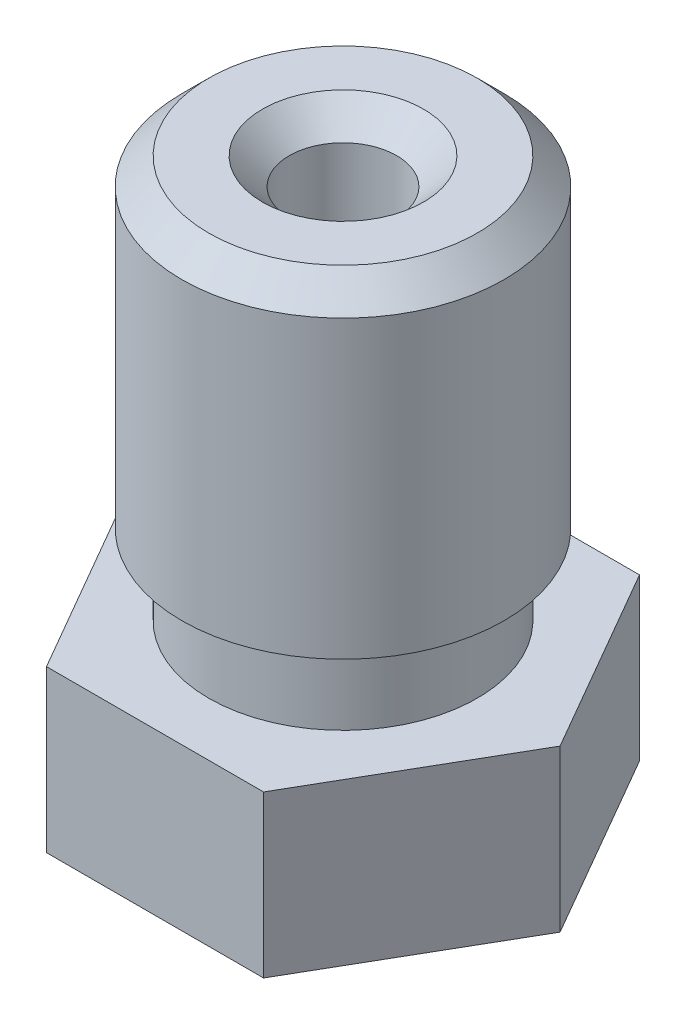
SolidWorks part; units mm, degrees
ref_plane "Спереди" through (0, 0, 0) normal (0, 0, 1) x (1, 0, 0)
ref_plane "Сверху" through (0, 0, 0) normal (0, 1, 0) x (1, 0, 0)
ref_plane "Справа" through (0, 0, 0) normal (1, 0, 0) x (0, 0, -1)
ref_plane "Плоскость1" through (0, 0, 0) normal (0, 0, -1) x (-1, 0, 0)
sketch "Эскиз1" plane through (0, 0, 0) normal (0, 0, -1) x (-1, 0, 0)
  line L0 (-3, 4.5) -> (0, 4.5)
  line L1 (0, 4.5) -> (0, 10.5)
  line L2 (0, 10.5) -> (-3, 10.5)
  line L3 (-3, 10.5) -> (-3, 4.5)
  line L4 (0, 4.5) -> (0, 10.5) construction
revolve "Повернуть1" add sketch "Эскиз1" angle 360 about L4
sketch "Эскиз2" plane through (0, 4.5, 0) normal (0, -1, 0) x (1, 0, 0)
  circle A0 centre (0, 0) radius 2.5
extrude "Бобышка-Вытянуть1" add sketch "Эскиз2" along normal blind 1.5
ref_plane "Плоскость2" through (0, 3, 0) normal (0, 1, 0) x (1, 0, 0)
sketch "Эскиз3" plane through (0, 3, 0) normal (0, 1, 0) x (1, 0, 0)
  line L0 (-2.0207, -3.5) -> (2.0207, -3.5)
  line L1 (2.0207, -3.5) -> (4.0415, 0)
  line L2 (4.0415, 0) -> (2.0207, 3.5)
  line L3 (2.0207, 3.5) -> (-2.0207, 3.5)
  line L4 (-2.0207, 3.5) -> (-4.0415, 0)
  line L5 (-4.0415, 0) -> (-2.0207, -3.5)
extrude "Бобышка-Вытянуть2" add sketch "Эскиз3" against normal blind 3
sketch "Эскиз4" plane through (0, 0, 0) normal (0, -1, 0) x (1, 0, 0)
  circle A0 centre (0, 0) radius 2.5
extrude "Бобышка-Вытянуть3" add sketch "Эскиз4" along normal blind 2 draft 45
sketch "Эскиз5" plane through (0, -2, 0) normal (0, -1, 0) x (1, 0, 0)
  circle A0 centre (0, 0) radius 0.2
extrude "Вырез-Вытянуть1" cut sketch "Эскиз5" against normal blind 0.8
sketch "Эскиз6" plane through (0, -1.2, 0) normal (0, -1, 0) x (1, 0, 0)
  circle A0 centre (0, 0) radius 0.2
extrude "Вырез-Вытянуть2" cut sketch "Эскиз6" against normal blind 0.5 draft 47.726 draft outward yes
sketch "Эскиз7" plane through (0, -0.7, 0) normal (0, -1, 0) x (1, 0, 0)
  circle A0 centre (0, 0) radius 0.75
extrude "Вырез-Вытянуть3" cut sketch "Эскиз7" against normal blind 0.4727
sketch "Эскиз8" plane through (0, -0.2273, 0) normal (0, -1, 0) x (1, 0, 0)
  circle A0 centre (0, 0) radius 0.75
extrude "Вырез-Вытянуть4" cut sketch "Эскиз8" against normal blind 0.2273 draft 47.726 draft outward yes
sketch "Эскиз9" plane through (0, 10.5, 0) normal (0, 1, 0) x (-1, 0, 0)
  circle A0 centre (0, 0) radius 1
extrude "Вырез-Вытянуть5" cut sketch "Эскиз9" against normal blind 10.5
chamfer "Фаска1" distance 0.5 angle 45 2 edges at (0, 10.5, -1) (0, 10.5, 3)
